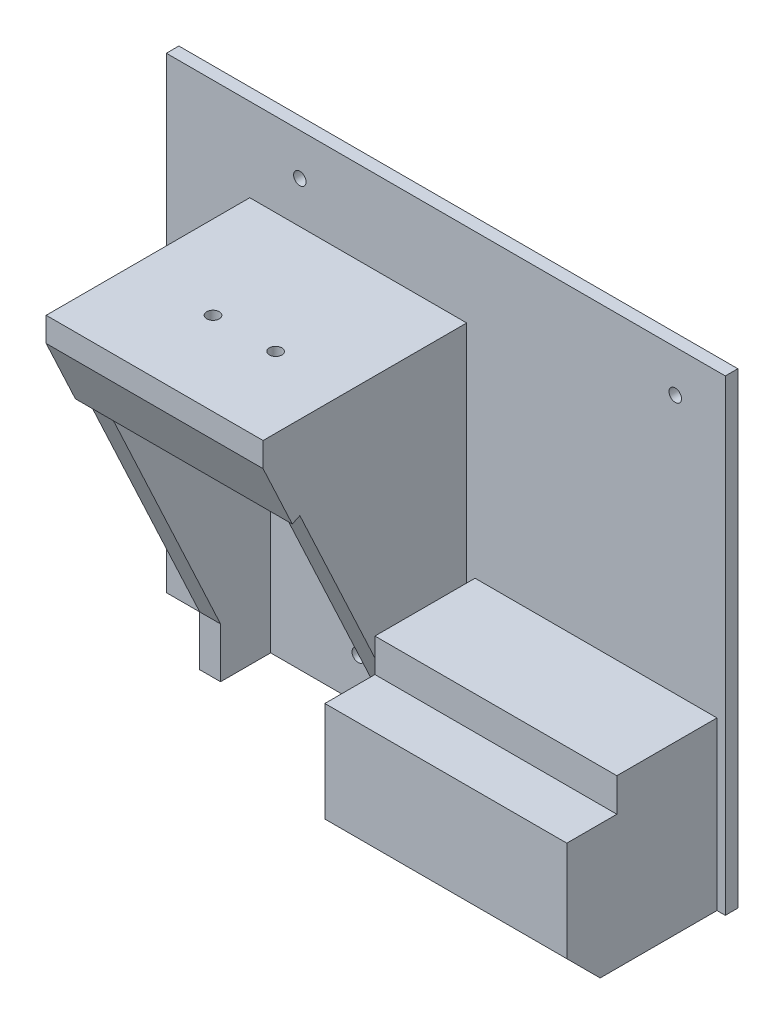
SolidWorks part; units mm, degrees
ref_plane "Front" through (0, 0, 0) normal (0, 0, 1) x (1, 0, 0)
ref_plane "Top" through (0, 0, 0) normal (0, 1, 0) x (1, 0, 0)
ref_plane "Right" through (0, 0, 0) normal (1, 0, 0) x (0, 0, -1)
sketch "Sketch1" plane through (0, 0, 0) normal (0, 0, 1) x (1, 0, 0)
  line L1 (-36, -46) -> (36, -46)
  line L2 (-36, -46) -> (-36, 46)
  line L3 (-36, 46) -> (36, 46)
  line L4 (36, -46) -> (36, 46)
  line L5 (-36, -46) -> (36, 46) construction
  line L6 (-36, 46) -> (36, -46) construction
  point P0 (0, 0)
  dimension "D1" = 92
  dimension "D2" = 72
extrude "Boss-Extrude1" add sketch "Sketch1" along normal blind 3
sketch "Sketch2" plane through (0, 0, 3) normal (0, 0, 1) x (1, 0, 0)
  line L0 (36, 46) -> (-36, 46) construction
  line L1 (36, -46) -> (31, -46)
  line L2 (36, -46) -> (36, 46)
  line L3 (36, 46) -> (31, 46)
  line L4 (31, -46) -> (31, 46)
  line L5 (36, -46) -> (31, 46) construction
  line L6 (36, 46) -> (31, -46) construction
  line L7 (-36, -46) -> (36, -46) construction
  line L8 (-11, -46) -> (-16, -46)
  line L9 (-11, -46) -> (-11, 46)
  line L10 (-11, 46) -> (-16, 46)
  line L11 (-16, -46) -> (-16, 46)
  line L12 (-11, -46) -> (-16, 46) construction
  line L13 (-11, 46) -> (-16, -46) construction
  point P4 (33.5, 0)
  point P12 (-13.5, 0)
  dimension "D1" = 5
  dimension "D2" = 5
  dimension "D3" = 42
extrude "Boss-Extrude2" add sketch "Sketch2" along normal blind 47
sketch "Sketch3" plane through (0, 0, 50) normal (0, 0, 1) x (1, 0, 0)
  line L0 (36, -46) -> (36, 46) construction
  line L1 (-16, 46) -> (36, 46)
  line L2 (-16, 46) -> (-16, 26)
  line L3 (-16, 26) -> (36, 26)
  line L4 (36, 46) -> (36, 26)
  line L5 (-16, 46) -> (36, 26) construction
  line L6 (-16, 26) -> (36, 46) construction
  point P4 (10, 36)
  dimension "D1" = 20
extrude "Boss-Extrude3" add sketch "Sketch3" against normal up to next
sketch "Sketch7" plane through (-16, 0, 0) normal (-1, 0, 0) x (0, 0, 1)
  line L0 (50, 41) -> (15, -34)
  line L1 (50, 46) -> (50, -46) construction
  line L5 (50, 46) -> (3, 46) construction
  line L6 (50, 41) -> (50, -46)
  line L8 (50, -46) -> (50, 26) construction
  line L9 (50, -46) -> (50, 26)
  line L10 (15, -34) -> (15, -46)
  line L11 (50, -46) -> (3, -46) construction
  line L12 (15, -46) -> (50, -46)
  line L14 (3, 46) -> (3, -46) construction
  point P1 (14.2571, -33.5271)
  line M3 (3, -46) -> (50, -46)
  line M4 (50, -46) -> (50, 46)
  dimension "D1" = 12
  dimension "D2" = 5
  dimension "D3" = 12
extrude "Cut-Extrude3" cut sketch "Sketch7" against normal up to next contours L6 L0 M4 M3
sketch "Sketch8" plane through (0, -11.8285, 25.3467) normal (0, -0.4229, 0.9062) x (1, 0, 0)
  line L0 (36, -24.4669) -> (36, 58.2978) construction
  line L1 (-16, 58.2978) -> (36, 58.2978)
  line L2 (-16, 58.2978) -> (-16, 41.7448)
  line L3 (-16, 41.7448) -> (36, 41.7448)
  line L4 (36, 58.2978) -> (36, 41.7448)
  line L5 (-16, 58.2978) -> (36, 41.7448) construction
  line L6 (-16, 41.7448) -> (36, 58.2978) construction
  line L7 (31, 41.7448) -> (-11, 41.7448) construction
  point P4 (10, 50.0213)
extrude "Boss-Extrude5" add sketch "Sketch8" along normal blind 2
sketch "Sketch9" plane through (0, 0, 50) normal (0, 0, 1) x (1, 0, 0)
  line L0 (36, 40.1542) -> (-16, 40.1542) construction
  line L1 (36, 40.1542) -> (-16, 40.1542)
  line L3 (-16, 40.1542) -> (36, 40.1542)
  line L4 (-16, 40.1542) -> (-16, 46)
  line L5 (-16, 46) -> (36, 46)
  line L6 (36, 40.1542) -> (36, 46)
  line L7 (-16, 40.1542) -> (36, 46) construction
  line L8 (-16, 46) -> (36, 40.1542) construction
  point P5 (10, 43.0771)
  line M1 (-16, 41) -> (36, 41)
  line M2 (36, 41) -> (36, 46)
  line M3 (36, 46) -> (-16, 46)
  line M4 (-16, 46) -> (-16, 41)
extrude "Boss-Extrude6" add sketch "Sketch9" along normal up to vertex (1.8124 mm away) contours M4 M1 M2 M3 | L1 L6 L4 M1 up to point (-16, 40.1542, 51.8124)
sketch "Sketch10" plane through (0, 26, 0) normal (0, -1, 0) x (1, 0, 0)
  line L4 (31, 43) -> (-11, 43)
  line L5 (-11, 43) -> (-11, 3)
  line L6 (-11, 3) -> (31, 3)
  line L7 (31, 3) -> (31, 43)
  line L8 (31, 43) -> (-11, 43)
  line L9 (-11, 43) -> (-11, 3)
  line L10 (-11, 3) -> (31, 3)
  line L11 (31, 3) -> (31, 43)
  dimension "D1" = 0
extrude "Cut-Extrude4" cut sketch "Sketch10" against normal blind 17
sketch "Sketch12" plane through (0, 46, 0) normal (0, 1, 0) x (1, 0, 0)
  line L0 (-16, -31.8124) -> (36, -31.8124) construction
  line L1 (-16, -51.8124) -> (-16, -3) construction
  line L2 (36, -51.8124) -> (36, 0) construction
  line L3 (36, -51.8124) -> (-16, -51.8124) construction
  circle A0 centre (4, -31.8124) radius 1.5
  circle A1 centre (19, -31.8124) radius 1.5
  dimension "D2" = 3
  dimension "D3" = 3
  dimension "D4" = 20
  dimension "D5" = 15
  dimension "D1" = 20
extrude "Cut-Extrude5" cut sketch "Sketch12" against normal up to next
sketch "Sketch13" plane through (0, 46, 0) normal (0, 1, 0) x (1, 0, 0)
  line L1 (36, 0) -> (-36, 0)
  line L2 (36, 0) -> (36, -3)
  line L3 (36, -3) -> (-36, -3)
  line L4 (-36, 0) -> (-36, -3)
  line L5 (36, 0) -> (-36, -3) construction
  line L6 (36, -3) -> (-36, 0) construction
  point P4 (0, -1.5)
extrude "Boss-Extrude7" add sketch "Sketch13" along normal blind 20
sketch "Sketch15" plane through (36, 0, 0) normal (1, 0, 0) x (0, 0, -1)
  line L1 (0, -46) -> (-3, -46)
  line L2 (0, -46) -> (0, 66)
  line L3 (0, 66) -> (-3, 66)
  line L4 (-3, -46) -> (-3, 66)
  line L5 (0, -46) -> (-3, 66) construction
  line L6 (0, 66) -> (-3, -46) construction
  point P4 (-1.5, 10)
extrude "Boss-Extrude8" add sketch "Sketch15" along normal blind 62
sketch "Sketch17" plane through (0, 0, 3) normal (0, 0, 1) x (1, 0, 0)
  line L0 (98, -46) -> (36, -46) construction
  line L1 (96, -46) -> (38, -46)
  line L2 (96, -46) -> (96, -6)
  line L3 (96, -6) -> (38, -6)
  line L4 (38, -46) -> (38, -6)
  line L5 (96, -46) -> (38, -6) construction
  line L6 (96, -6) -> (38, -46) construction
  line L7 (98, 66) -> (98, -46) construction
  point P4 (67, -26)
  dimension "D1" = 40
  dimension "D2" = 58
  dimension "D3" = 2
extrude "Boss-Extrude9" add sketch "Sketch17" along normal blind 36
chamfer "Chamfer1" distance 8 angle 45 1 edges at (67, -46, 39)
sketch "Sketch18" plane through (0, 0, 39) normal (0, 0, 1) x (1, 0, 0)
  line L0 (96, -38) -> (96, -6) construction
  line L1 (38, -6) -> (96, -6)
  line L2 (38, -6) -> (38, -14)
  line L3 (38, -14) -> (96, -14)
  line L4 (96, -6) -> (96, -14)
  line L5 (38, -6) -> (96, -14) construction
  line L6 (38, -14) -> (96, -6) construction
  point P4 (67, -10)
  dimension "D1" = 8
extrude "Cut-Extrude8" cut sketch "Sketch18" against normal blind 12
sketch "Sketch14" plane through (0, 0, 3) normal (0, 0, 1) x (1, 0, 0)
  line L0 (-36, 66) -> (98, 66) construction
  line L2 (-11, -46) -> (31, -46) construction
  line L5 (98, 66) -> (98, -46) construction
  line L6 (-36, 66) -> (-36, -46) construction
  line L9 (-11, -46) -> (-11, 43) construction
  circle A0 centre (86, 56) radius 1.5
  circle A1 centre (10, -36) radius 1.5
  circle A2 centre (-4, 56) radius 1.5
  point P12 (0, 0)
  point P17 (9.3469, -36)
  dimension "D1" = 3
  dimension "D4" = 3
  dimension "D6" = 3
  dimension "D7" = 21
  dimension "D8" = 32
  dimension "D2" = 10
  dimension "D3" = 12
  dimension "D5" = 10
extrude "Cut-Extrude9" cut sketch "Sketch14" against normal up to next
